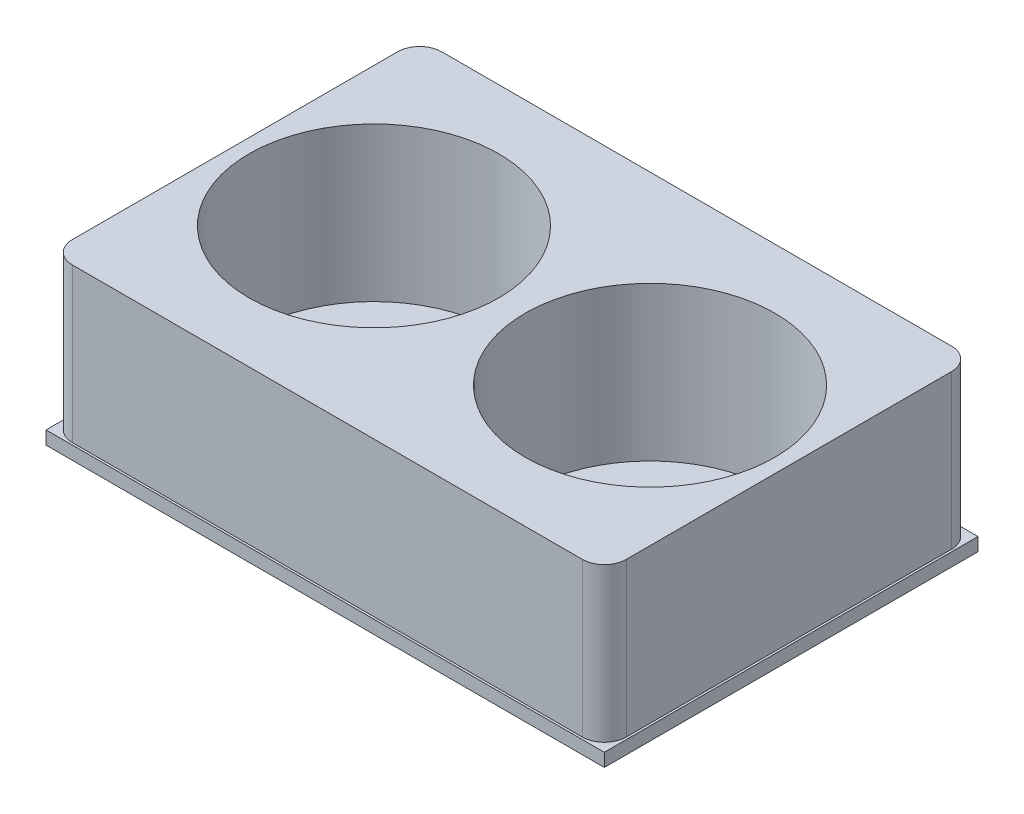
SolidWorks part; units mm, degrees
ref_plane "Front Plane" through (0, 0, 0) normal (0, 0, 1) x (1, 0, 0)
ref_plane "Top Plane" through (0, 0, 0) normal (0, 1, 0) x (1, 0, 0)
ref_plane "Right Plane" through (0, 0, 0) normal (1, 0, 0) x (0, 0, -1)
sketch "Sketch2" plane through (0, 0, 0) normal (0, 1, 0) x (1, 0, 0)
  line L0 (0, 42) -> (1, 42) construction
  line L1 (0, 0) -> (126, 0)
  line L2 (0, 0) -> (0, 84)
  line L3 (0, 84) -> (126, 84)
  line L4 (126, 0) -> (126, 84)
  line L5 (1, 42) -> (62.2, 42) construction
  line L6 (62.2, 42) -> (63.8, 42) construction
  line L7 (63.8, 42) -> (125, 42) construction
  circle A0 centre (31.6, 42) radius 28.4
  circle A1 centre (94.4, 42) radius 28.4
  dimension "D7" = 56.8
  dimension "D8" = 56.8
  dimension "D1" = 84
  dimension "D2" = 126
  dimension "D3" = 1
  dimension "D4" = 61.2
  dimension "D5" = 1.6
  dimension "D6" = 61.2
extrude "Boss-Extrude1" add sketch "Sketch2" along normal blind 35
sketch "Sketch3" plane through (0, 0, 0) normal (0, -1, 0) x (1, 0, 0)
  line L0 (0, -42) -> (126, -42) construction
  line L1 (0, -84) -> (0, 0) construction
  line L2 (126, 0) -> (126, -84) construction
  line L3 (63, -84) -> (63, 0) construction
  line L4 (126, -84) -> (0, -84) construction
  line L5 (0, 0) -> (126, 0) construction
  line L7 (-0.5, -84.5) -> (126.5, -84.5)
  line L8 (-0.5, -84.5) -> (-0.5, 0.5)
  line L9 (-0.5, 0.5) -> (126.5, 0.5)
  line L10 (126.5, -84.5) -> (126.5, 0.5)
  line L11 (-0.5, -84.5) -> (126.5, 0.5) construction
  line L12 (-0.5, 0.5) -> (126.5, -84.5) construction
  point P12 (63, -42)
  dimension "D1" = 127
  dimension "D2" = 85
extrude "Boss-Extrude2" add sketch "Sketch3" along normal blind 3 contours L8 L7 L10 L9
fillet "Fillet1" radius 5 4 edges at (0, 17.5, -84) (126, 17.5, -84) (126, 17.5, 0) (0, 17.5, 0)
